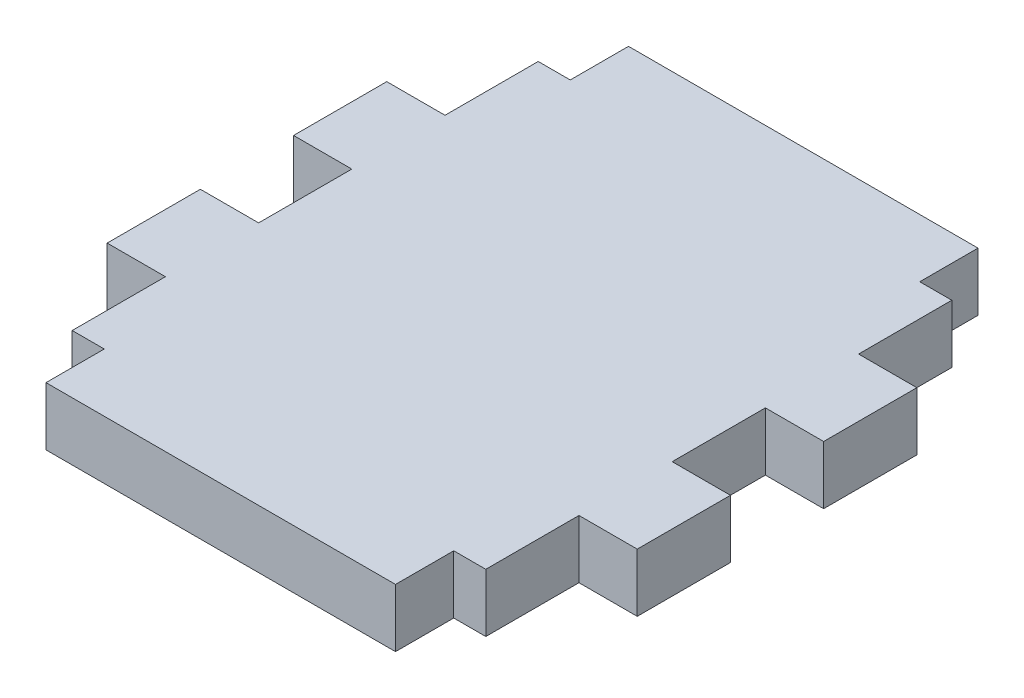
SolidWorks part; units mm, degrees
ref_plane "Front" through (0, 0, 0) normal (0, 0, 1) x (1, 0, 0)
ref_plane "Top" through (0, 0, 0) normal (0, 1, 0) x (1, 0, 0)
ref_plane "Right" through (0, 0, 0) normal (1, 0, 0) x (0, 0, -1)
sketch "Esboço1" plane through (0, 0, 0) normal (0, 1, 0) x (1, 0, 0)
  line L1 (-56.4007, 6.4605) -> (-56.4007, 9.4605)
  line L2 (-56.4007, 9.4605) -> (-38.4007, 9.4605)
  line L3 (-38.4007, 9.4605) -> (-38.4007, 6.4605)
  line L7 (-38.4007, -17.5395) -> (-38.4007, -20.5395)
  line L8 (-38.4007, -20.5395) -> (-56.4007, -20.5395)
  line L9 (-56.4007, -20.5395) -> (-56.4007, -17.5395)
  line L12 (-56.4007, 6.4605) -> (-58.0507, 6.4605)
  line L24 (-61.0507, -3.1395) -> (-58.0507, -3.1395)
  line L25 (-58.0507, -3.1395) -> (-58.0507, -7.9395)
  line L26 (-58.0507, -7.9395) -> (-61.0507, -7.9395)
  line L40 (-36.7507, 6.4605) -> (-36.7507, 1.6605)
  line L43 (-36.7507, 1.6605) -> (-33.7507, 1.6605)
  line L44 (-33.7507, 1.6605) -> (-33.7507, -3.1395)
  line L45 (-33.7507, -3.1395) -> (-36.7507, -3.1395)
  line L46 (-36.7507, -3.1395) -> (-36.7507, -7.9395)
  line L47 (-36.7507, -7.9395) -> (-33.7507, -7.9395)
  line L48 (-33.7507, -7.9395) -> (-33.7507, -12.7395)
  line L49 (-33.7507, -12.7395) -> (-36.7507, -12.7395)
  line L55 (-58.0507, 6.4605) -> (-58.0507, 1.6605)
  line L56 (-61.0507, 1.6605) -> (-58.0507, 1.6605)
  line L57 (-56.4007, -17.5395) -> (-58.0507, -17.5395)
  line L58 (-58.0507, -17.5395) -> (-58.0507, -12.7395)
  line L59 (-58.0507, -12.7395) -> (-61.0507, -12.7395)
  line L60 (-38.4007, -17.5395) -> (-36.7507, -17.5395)
  line L61 (-36.7507, -17.5395) -> (-36.7507, -12.7395)
  line L63 (-38.4007, 6.4605) -> (-36.7507, 6.4605)
  line L66 (-61.0507, 1.6605) -> (-61.0507, -3.1395)
  line L67 (-61.0507, -7.9395) -> (-61.0507, -12.7395)
  dimension "D1" = 18
  dimension "D2" = 18
  dimension "D3" = 3
  dimension "D4" = 4.8
  dimension "D5" = 24
  dimension "D6" = 3
  dimension "D7" = 3
  dimension "D8" = 1.65
  dimension "D9" = 3
  dimension "D10" = 3
  dimension "D11" = 1.65
  dimension "D12" = 3
  dimension "D13" = 38.4007
  dimension "D14" = 3
  dimension "D16" = 3
  dimension "D17" = 4.8
  dimension "D18" = 1.65
  dimension "D19" = 3
  dimension "D20" = 3
  dimension "D21" = 3
  dimension "D22" = 4.8
  dimension "D23" = 4.8
  dimension "D24" = 4.8
  dimension "D25" = 3
  dimension "D26" = 1.65
extrude "Ressalto-extrusão1" add sketch "Esboço1" along normal blind 3
